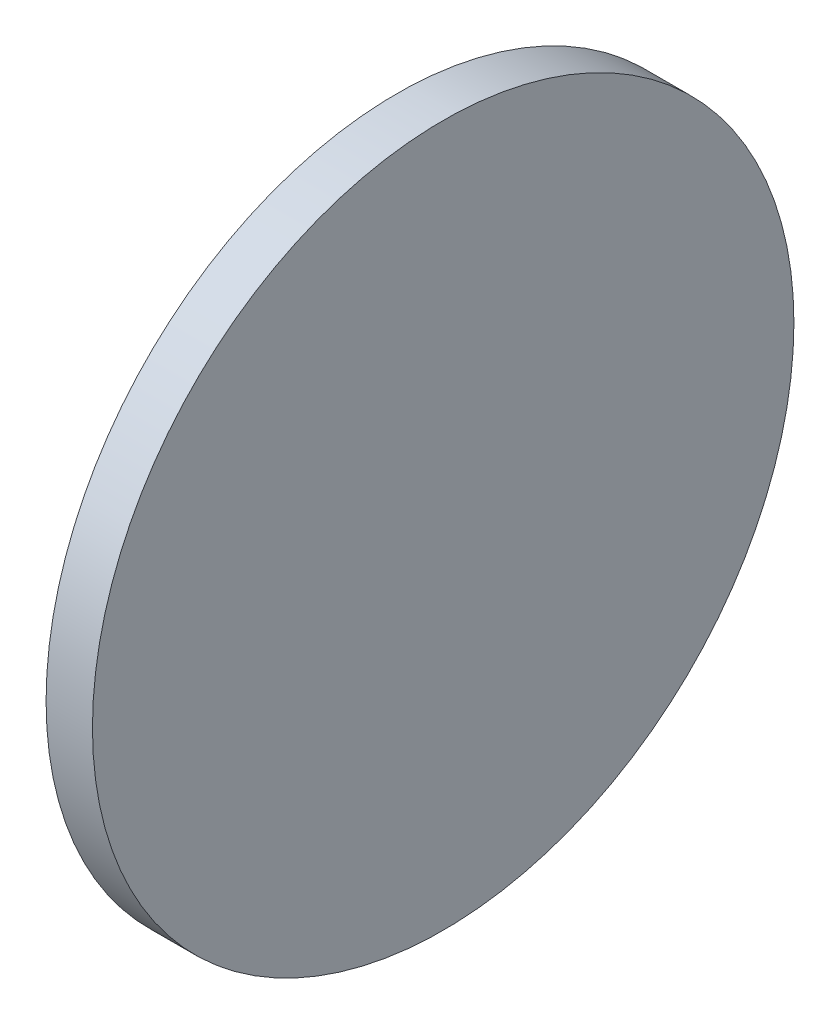
SolidWorks part; units mm, degrees
ref_plane "Front Plane" through (0, 0, 0) normal (0, 0, 1) x (1, 0, 0)
ref_plane "Top Plane" through (0, 0, 0) normal (0, 1, 0) x (1, 0, 0)
ref_plane "Right Plane" through (0, 0, 0) normal (1, 0, 0) x (0, 0, -1)
sketch "Sketch1" plane through (0, 0, 0) normal (0, 1, 0) x (1, 0, 0)
  line L1 (-0.7874, 11.9126) -> (0.7874, 11.9126)
  line L2 (-0.7874, 11.9126) -> (-0.7874, 0)
  line L3 (-0.7874, 0) -> (0.7874, 0)
  line L4 (0.7874, 11.9126) -> (0.7874, 0)
  dimension "D1" = 11.9126
  dimension "D2" = 1.5748
revolve "Revolve1" add sketch "Sketch1" angle 360 about L3
